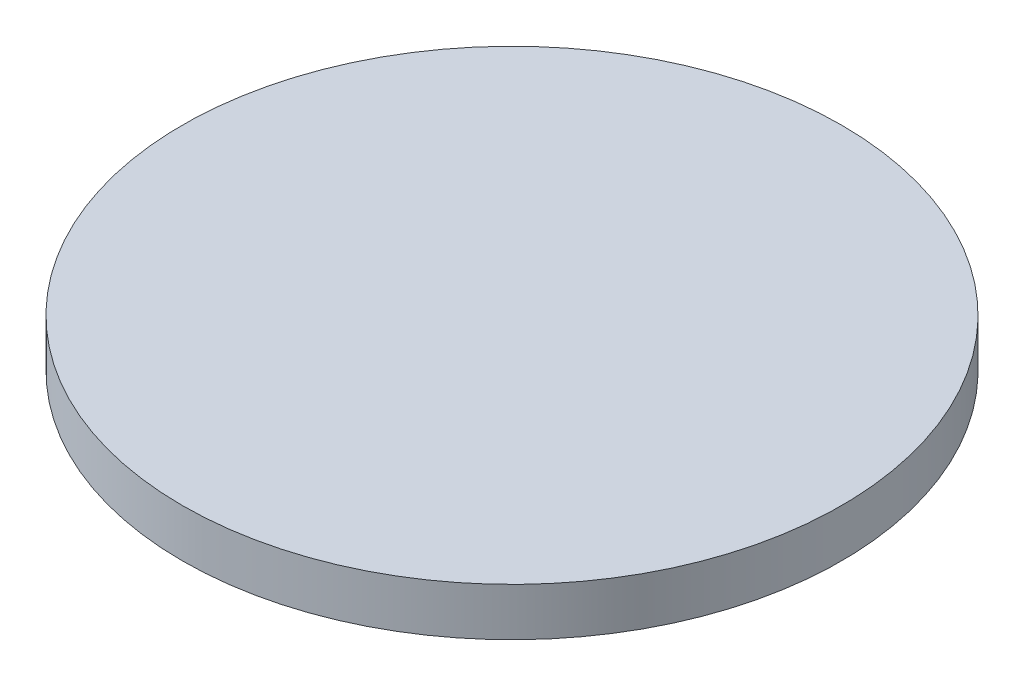
SolidWorks part; units mm, degrees
ref_plane "Front Plane" through (0, 0, 0) normal (0, 0, 1) x (1, 0, 0)
ref_plane "Top Plane" through (0, 0, 0) normal (0, 1, 0) x (1, 0, 0)
ref_plane "Right Plane" through (0, 0, 0) normal (1, 0, 0) x (0, 0, -1)
sketch "Sketch1" plane through (0, 0, 0) normal (0, 1, 0) x (1, 0, 0)
  circle A0 centre (0, 0) radius 13.97
  dimension "D1" = 27.94
extrude "Boss-Extrude1" add sketch "Sketch1" along normal blind 2.032
